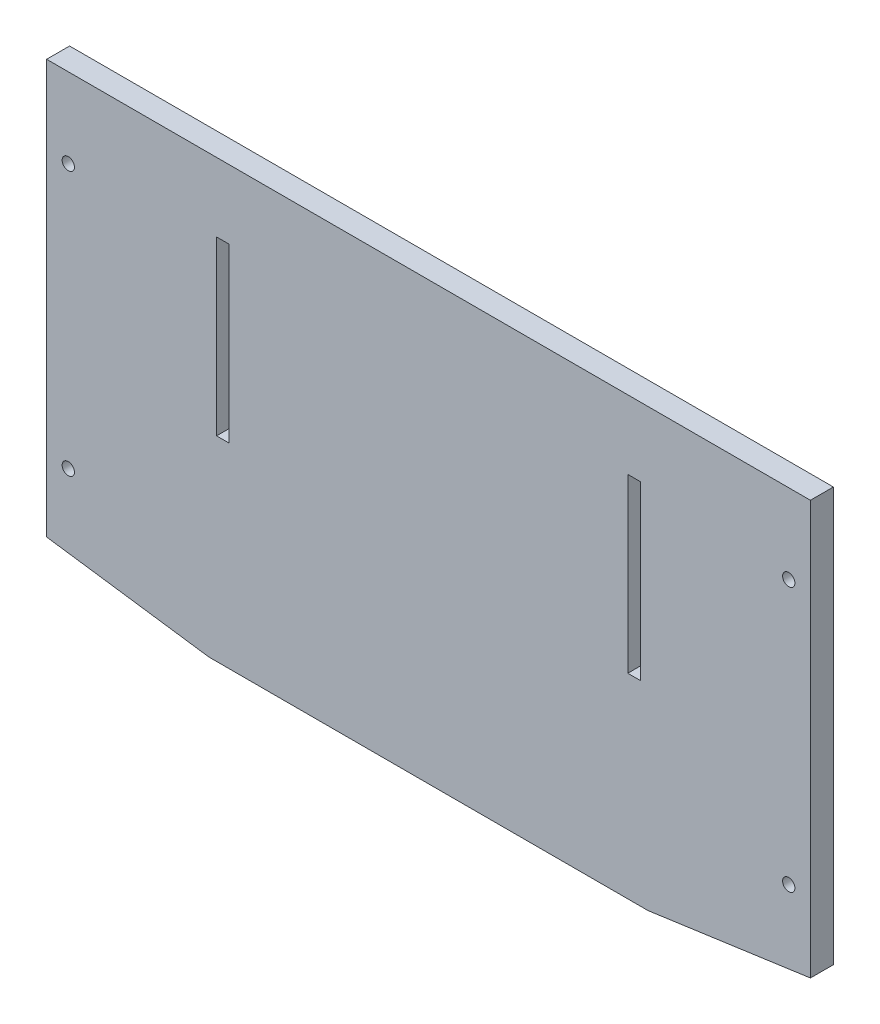
SolidWorks part; units mm, degrees
material "Acrylic (Medium-high impact)"
ref_plane "Front Plane" through (0, 0, 0) normal (0, 0, 1) x (1, 0, 0)
ref_plane "Top Plane" through (0, 0, 0) normal (0, 1, 0) x (1, 0, 0)
ref_plane "Right Plane" through (0, 0, 0) normal (1, 0, 0) x (0, 0, -1)
sketch "Sketch1" plane through (0, 0, 0) normal (0, 0, 1) x (1, 0, 0)
  line L1 (211.1756, 127) -> (0, 127)
  line L2 (211.1756, 127) -> (211.1756, 0)
  line L3 (211.1756, 0) -> (0, 0)
  line L4 (0, 127) -> (0, 0)
  line L5 (211.1756, 127) -> (0, 0) construction
  line L6 (211.1756, 0) -> (0, 127) construction
  point P0 (105.5878, 63.5)
  dimension "D1" = 127
  dimension "D2" = 211.1756
extrude "Boss-Extrude1" add sketch "Sketch1" along normal blind 6.35
hole_wizard "M3 Clearance Hole1" positions "Sketch2" profile "Sketch3" hole size "M3" standard "ANSI Metric" end condition through all
sketch "Sketch2" plane through (0, 0, 6.35) normal (0, 0, 1) x (1, 0, 0)
  line L0 (0, 127) -> (0, 0) construction
  line L1 (211.1756, 127) -> (0, 127) construction
  line L2 (211.1756, 0) -> (211.1756, 127) construction
  point P0 (5.9944, 105.0036)
  point P2 (5.9944, 31.9786)
  point P4 (205.1812, 31.9786)
  point P6 (205.1812, 105.0036)
  dimension "D1" = 5.9944
  dimension "D2" = 21.9964
  dimension "D3" = 5.9944
  dimension "D4" = 73.025
sketch "Sketch3" plane through (5.9944, 105.0036, 6.35) normal (1, 0, 0) x (0, -1, 0)
  line L0 (0, 0) -> (0, 6.35)
  line L1 (0, 6.35) -> (1.7, 6.35)
  line L2 (1.7, 6.35) -> (1.7, 0)
  line L5 (1.7, 0) -> (0, 0)
  line L11 (0, -6.35) -> (0, 107.95) construction
  dimension "Thru Hole Dia." = 3.4
  dimension "Thru Hole Depth" = 6.35
sketch "Sketch4" plane through (0, 0, 6.35) normal (0, 0, 1) x (1, 0, 0)
  line L0 (0, 127) -> (0, 0) construction
  line L1 (46.99, 107.95) -> (50.4952, 107.95)
  line L2 (46.99, 107.95) -> (46.99, 60.325)
  line L3 (46.99, 60.325) -> (50.4952, 60.325)
  line L4 (50.4952, 107.95) -> (50.4952, 60.325)
  line L5 (160.6804, 107.95) -> (164.1856, 107.95)
  line L6 (160.6804, 107.95) -> (160.6804, 60.325)
  line L7 (160.6804, 60.325) -> (164.1856, 60.325)
  line L8 (164.1856, 107.95) -> (164.1856, 60.325)
  line L9 (211.1756, 0) -> (211.1756, 127) construction
  line L10 (211.1756, 127) -> (0, 127) construction
  dimension "D1" = 3.5052
  dimension "D2" = 47.625
  dimension "D3" = 46.99
  dimension "D4" = 46.99
  dimension "D5" = 19.05
extrude "Cut-Extrude1" cut sketch "Sketch4" against normal through all
sketch "Sketch5" plane through (0, 0, 6.35) normal (0, 0, 1) x (1, 0, 0)
  line L0 (0, 12.6083) -> (89.7128, 0)
  line L1 (0, 127) -> (0, 0) construction
  line L2 (0, 0) -> (211.1756, 0) construction
  line L3 (89.7128, 0) -> (0, 0)
  line L4 (0, 0) -> (0, 12.6083)
  line L5 (121.4628, 0) -> (211.1756, 0)
  line L6 (211.1756, 0) -> (211.1756, 12.6083)
  line L7 (211.1756, 0) -> (211.1756, 127) construction
  line L8 (211.1756, 12.6083) -> (121.4628, 0)
  dimension "D1" = 8
  dimension "D2" = 8
  dimension "D3" = 31.75
extrude "Cut-Extrude2" cut sketch "Sketch5" against normal through all
sketch "Sketch6" plane through (0, 0, 6.35) normal (0, 0, 1) x (1, 0, 0)
  line L1 (44.8564, -0.0458) -> (166.3192, -0.0458)
  line L2 (44.8564, -0.0458) -> (44.8564, 6.3042)
  line L3 (44.8564, 6.3042) -> (166.3192, 6.3042)
  line L4 (166.3192, -0.0458) -> (166.3192, 6.3042)
  line L5 (211.1756, 12.6083) -> (121.4628, 0) construction
  line L6 (89.7128, 0) -> (0, 12.6083) construction
  point P5 (89.7128, 0)
  point P6 (121.4628, 0)
  point P7 (89.7128, 6.35)
  point P10 (166.3192, 6.3042)
  point P13 (43.4873, 6.4966)
  dimension "D1" = 6.35
extrude "Cut-Extrude3" cut sketch "Sketch6" against normal through all
